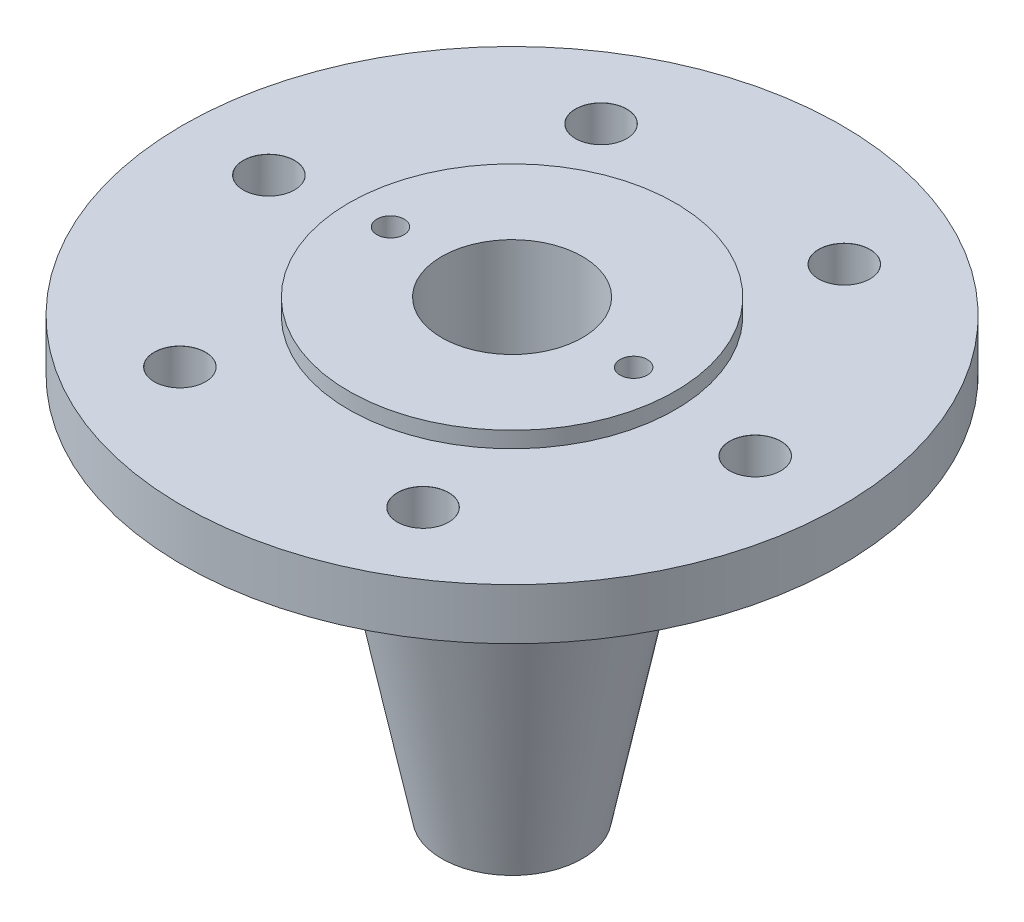
SolidWorks part; units mm, degrees
ref_plane "Front Plane" through (0, 0, 0) normal (0, 0, 1) x (1, 0, 0)
ref_plane "Top Plane" through (0, 0, 0) normal (0, 1, 0) x (1, 0, 0)
ref_plane "Right Plane" through (0, 0, 0) normal (1, 0, 0) x (0, 0, -1)
sketch "Sketch1" plane through (0, 0, 0) normal (0, 0, 1) x (1, 0, 0)
  line L0 (0, 0) -> (51, 0)
  line L1 (51, 0) -> (51, -5)
  line L2 (51, -5) -> (103, -5)
  line L3 (103, -5) -> (103, -21)
  line L4 (103, -21) -> (54, -21)
  line L5 (54, -21) -> (54, -31)
  line L6 (54, -31) -> (44, -31)
  line L7 (44, -31) -> (22, -141)
  line L8 (22, -141) -> (0, -141)
  line L9 (0, 0) -> (0, -141) construction
  line L10 (0, 0) -> (0, -141)
  dimension "D1" = 206
  dimension "D2" = 44
  dimension "D3" = 108
  dimension "D4" = 102
  dimension "D5" = 88
  dimension "D6" = 5
  dimension "D7" = 16
  dimension "D8" = 10
  dimension "D9" = 120
revolve "Revolve1" add sketch "Sketch1" angle 360 about L9
sketch "Sketch2" plane through (0, 0, 0) normal (0, 0, 1) x (1, 0, 0)
  line L0 (0, 0) -> (0, -141) construction
  line L1 (-22, -141) -> (22, -141) construction
  line L2 (0, -141) -> (-11.75, -141) construction
  line L3 (-11.75, -141) -> (-11.75, -103)
  line L4 (-11, -83) -> (-16, -86.247)
  line L5 (-16, -86.247) -> (-16, -100.24)
  line L6 (-16, -100.24) -> (-11.75, -103)
  line L7 (-11, -83) -> (-11, -51.1435)
  line L8 (-11, -51.1435) -> (-22, -44)
  line L9 (-22, -44) -> (-22, 0)
  line L10 (51, 0) -> (-51, 0) construction
  line L11 (-22, 0) -> (0, 0) construction
  line L12 (-11.75, -141) -> (0, -141)
  line L13 (-22, 0) -> (0, 0)
  line L14 (0, 0) -> (0, -141)
  dimension "D1" = 44
  dimension "D2" = 44
  dimension "D3" = 33
  dimension "D4" = 22
  dimension "D5" = 23.5
  dimension "D6" = 38
  dimension "D7" = 33
  dimension "D8" = 20
  dimension "D9" = 33
  dimension "D10" = 32
revolve "Cut-Revolve1" cut sketch "Sketch2" angle 360 about L14
cosmetic thread "Cosmetic Thread1" parameters "D2"=25
fillet "Fillet1" radius 5 1 edges at (-44, -31, 0)
hole_wizard "Ø16.0 (16) Diameter Hole1" positions "Sketch3" profile "Sketch4" hole size "Ø16.0" standard "ANSI Metric" end condition up to next
sketch "Sketch3" plane through (0, -5, 0) normal (0, 1, 0) x (1, 0, 0)
  circle A0 centre (0, 0) radius 76 construction
  point P5 (-76, 0)
sketch "Sketch4" plane through (-76, -5, 0) normal (1, 0, 0) x (0, 0, 1)
  line L0 (0, 0) -> (0, 16)
  line L1 (0, 16) -> (8, 16)
  line L2 (8, 16) -> (8, 0.025)
  line L3 (8, 0.025) -> (8.025, 0)
  line L5 (8.025, 0) -> (0, 0)
  line L6 (-8, 0.025) -> (-8.025, 0) construction
  line L11 (0, -6.35) -> (0, 107.95) construction
  dimension "Thru Hole Dia." = 16
  dimension "Thru Hole Depth" = 16
  dimension "Near C'Sink Dia." = 16.05
  dimension "Near C'Sink Angle" = 90
pattern_circular "CirPattern1" count 6 over 360 about axis through (0, 0, 0) along (0, 1, 0) of "Ø16.0 (16) Diameter Hole1"
hole_wizard "M10x1.5 Tapped Hole1" positions "Sketch5" profile "Sketch6" tap size "M10x1.5" standard "ANSI Metric"
sketch "Sketch5" plane through (0, 0, 0) normal (0, 1, 0) x (1, 0, 0)
  circle A0 centre (0, 0) radius 38 construction
  point P5 (-38, 0)
  point P7 (38, 0)
sketch "Sketch6" plane through (38, 0, 0) normal (1, 0, 0) x (0, 0, 1)
  line L0 (0, 0) -> (0, 20.5537)
  line L1 (0, 20.5537) -> (4.25, 18)
  line L2 (4.25, 18) -> (4.25, 0)
  line L5 (4.25, 0) -> (0, 0)
  line L10 (0, 20.5537) -> (-4.25, 18) construction
  line L11 (0, -6.35) -> (0, 107.95) construction
  dimension "Tap Drill Dia." = 8.5
  dimension "Tap Drill Depth" = 18
  dimension "Drill Angle" = 118
cosmetic thread "Hole Thread1" parameters "D1"=15, "D2"=10
cosmetic thread "Hole Thread2" parameters "D1"=15, "D2"=10
